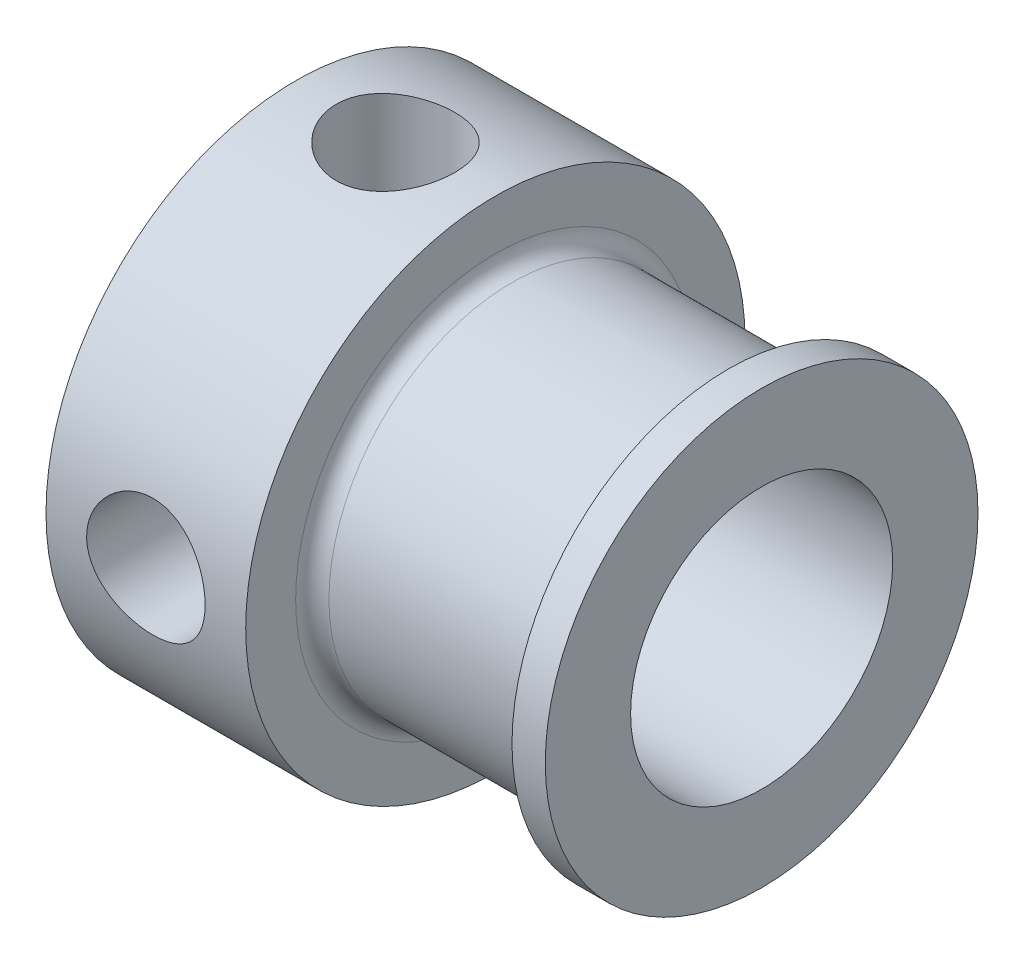
SolidWorks part; units mm, degrees
material "Cast Alloy Steel"
ref_plane "Front Plane" through (0, 0, 0) normal (0, 0, 1) x (1, 0, 0)
ref_plane "Top Plane" through (0, 0, 0) normal (0, 1, 0) x (1, 0, 0)
ref_plane "Right Plane" through (0, 0, 0) normal (1, 0, 0) x (0, 0, -1)
sketch "Sketch1" plane through (0, 0, 0) normal (1, 0, 0) x (0, 0, -1)
  circle A0 centre (0, 0) radius 4.7625
  circle A1 centre (0, 0) radius 2.5
  dimension "D1" = 5
  dimension "D2" = 9.525
extrude "Base" add sketch "Sketch1" along normal blind 8.89
sketch "Sketch2" plane through (0, 0, 0) normal (0, 0, 1) x (1, 0, 0)
  line L0 (8.89, 4.7625) -> (0, 4.7625) construction
  line L1 (3.81, 4.7625) -> (8.89, 4.7625)
  line L2 (3.81, 4.7625) -> (3.81, 3.4925)
  line L3 (3.81, 3.4925) -> (8.255, 3.4925)
  line L4 (8.255, 3.4925) -> (8.255, 4.1275)
  line L5 (0, 4.7625) -> (0, -4.7625) construction
  line L6 (8.255, 4.1275) -> (8.89, 4.1275)
  line L8 (8.89, 4.1275) -> (8.89, 4.7625)
  line L9 (8.89, -2.5) -> (8.89, 2.5) construction
  dimension "D1" = 3.81
  dimension "D2" = 0.635
  dimension "D3" = 1.27
  dimension "D4" = 0.635
ref_axis "Axis1" through (8.89, 0, 0) along (-1, 0, 0)
revolve "Spool" cut sketch "Sketch2" angle 360 about axis through (8.89, 0, 0) along (-1, 0, 0)
sketch "Sketch7" plane through (0, 0, 0) normal (0, 1, 0) x (1, 0, 0)
  line L0 (8.89, 0) -> (0, 0) construction
  line L1 (0, 4.7625) -> (0, -4.7625) construction
  circle A0 centre (1.905, 3.81) radius 0.3969
  dimension "D1" = 0.7937
  dimension "D2" = 3.81
  dimension "D3" = 1.905
extrude "CrimpHole" cut sketch "Sketch7" against normal through all and the other way through all
hole_wizard "ShaftSetScrew" positions "Sketch4" profile "Sketch3" tap size "#4-40" standard "ANSI Inch"
sketch "Sketch4" plane through (0, 0, 0) normal (0, 0, 1) x (1, 0, 0)
  line L0 (8.89, 0) -> (0, 0) construction
  line L1 (0, 4.7625) -> (0, -4.7625) construction
  point P0 (1.905, 0)
  dimension "D1" = 1.905
sketch "Sketch3" plane through (1.905, 0, 0) normal (1, 0, 0) x (0, 1, 0)
  line L0 (0, 0) -> (0, 4.7635)
  line L1 (0, 4.7635) -> (1.1303, 4.7635)
  line L2 (1.1303, 4.7635) -> (1.1303, 0)
  line L5 (1.1303, 0) -> (0, 0)
  line L11 (0, -6.35) -> (0, 107.95) construction
  dimension "Thread Major Dia." = 2.2606
  dimension "Thru Tap Drill Depth" = 4.7635
fillet "CutterRad" radius 0.3175 2 edges at (3.81, 0, -3.4925) (8.255, 0, -3.4925)
pattern_circular "CirPattern1" count 4 every 90 about axis through (8.89, 0, 0) along (-1, 0, 0) skipping 2 of "ShaftSetScrew"
